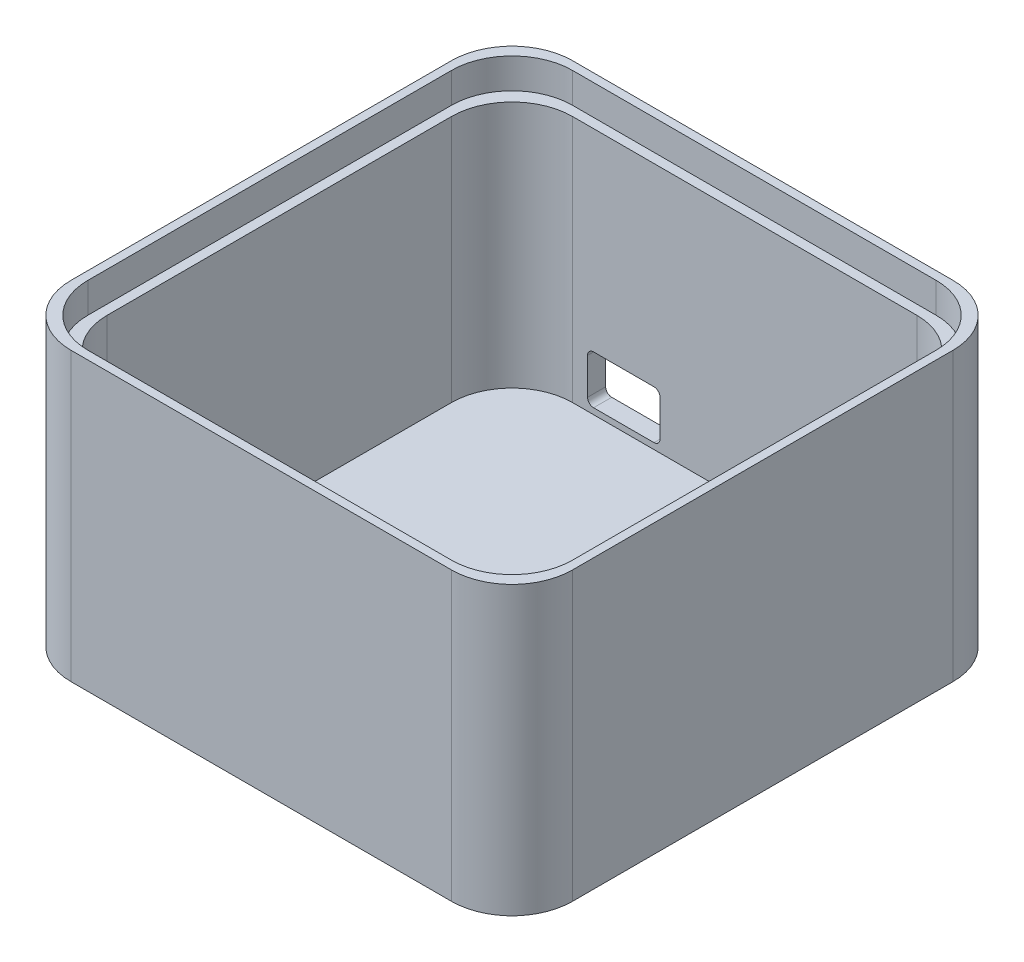
SolidWorks part; units mm, degrees
ref_plane "前视基准面" through (0, 0, 0) normal (0, 0, 1) x (1, 0, 0)
ref_plane "上视基准面" through (0, 0, 0) normal (0, 1, 0) x (1, 0, 0)
ref_plane "右视基准面" through (0, 0, 0) normal (1, 0, 0) x (0, 0, -1)
other "Configuration Table"
sketch "Sketch1" plane through (0, 0, 0) normal (0, 1, 0) x (1, 0, 0)
  line L1 (-30, 40) -> (30, 40)
  line L2 (-40, 30) -> (-40, -30)
  line L3 (-30, -40) -> (30, -40)
  line L4 (40, 30) -> (40, -30)
  line L5 (-40, 40) -> (40, -40) construction
  line L6 (-40, -40) -> (40, 40) construction
  line L7 (-31.5, 41.5) -> (31.5, 41.5)
  line L8 (-41.5, 31.5) -> (-41.5, -31.5)
  line L9 (-31.5, -41.5) -> (31.5, -41.5)
  line L10 (41.5, 31.5) -> (41.5, -31.5)
  line L11 (-41.5, 41.5) -> (41.5, -41.5) construction
  line L12 (-41.5, -41.5) -> (41.5, 41.5) construction
  line L13 (-28.5, 38.5) -> (28.5, 38.5)
  line L14 (-38.5, 28.5) -> (-38.5, -28.5)
  line L15 (-28.5, -38.5) -> (28.5, -38.5)
  line L16 (38.5, 28.5) -> (38.5, -28.5)
  line L17 (-38.5, 38.5) -> (38.5, -38.5) construction
  line L18 (-38.5, -38.5) -> (38.5, 38.5) construction
  arc A0 (30, -40) -> (40, -30) centre (30, -30) ccw
  arc A1 (28.5, -38.5) -> (38.5, -28.5) centre (28.5, -28.5) ccw
  arc A2 (31.5, -41.5) -> (41.5, -31.5) centre (31.5, -31.5) ccw
  arc A3 (-41.5, -31.5) -> (-31.5, -41.5) centre (-31.5, -31.5) ccw
  arc A4 (-40, -30) -> (-30, -40) centre (-30, -30) ccw
  arc A5 (-38.5, -28.5) -> (-28.5, -38.5) centre (-28.5, -28.5) ccw
  arc A6 (31.5, 41.5) -> (41.5, 31.5) centre (31.5, 31.5) cw
  arc A7 (30, 40) -> (40, 30) centre (30, 30) cw
  arc A8 (28.5, 38.5) -> (38.5, 28.5) centre (28.5, 28.5) cw
  arc A9 (-31.5, 41.5) -> (-41.5, 31.5) centre (-31.5, 31.5) ccw
  arc A10 (-30, 40) -> (-40, 30) centre (-30, 30) ccw
  arc A11 (-28.5, 38.5) -> (-38.5, 28.5) centre (-28.5, 28.5) ccw
  point P0 (0, 0)
  point P6 (0, 0)
  point P11 (0, 0)
  dimension "D7" = 10
  dimension "D1" = 80
  dimension "D2" = 80
  dimension "D3" = 1.5
  dimension "D4" = 1.5
  dimension "D5" = 3
  dimension "D6" = 3
extrude "Boss-Extrude1" add sketch "Sketch1" along normal blind 46 contours L7 A6 L10 A2 L9 A3 L8 A9 | L13 A8 L16 A1 L15 A5 L14 A11
sketch "Sketch2" plane through (0, 46, 0) normal (0, 1, 0) x (1, 0, 0)
  line L1 (-30.1, 40.1) -> (30.1, 40.1)
  line L2 (-40.1, 30.1) -> (-40.1, -30.1)
  line L3 (-30.1, -40.1) -> (30.1, -40.1)
  line L4 (40.1, 30.1) -> (40.1, -30.1)
  line L5 (-40.1, 40.1) -> (40.1, -40.1) construction
  line L6 (-40.1, -40.1) -> (40.1, 40.1) construction
  arc A0 (-40.1, -30.1) -> (-30.1, -40.1) centre (-30.1, -30.1) ccw
  arc A1 (30.1, -40.1) -> (40.1, -30.1) centre (30.1, -30.1) ccw
  arc A2 (30.1, 40.1) -> (40.1, 30.1) centre (30.1, 30.1) cw
  arc A3 (-30.1, 40.1) -> (-40.1, 30.1) centre (-30.1, 30.1) ccw
  point P0 (0, 0)
  dimension "D3" = 10
  dimension "D1" = 80.2
  dimension "D2" = 80.2
extrude "Cut-Extrude1" cut sketch "Sketch2" against normal blind 5
sketch "Sketch3" plane through (0, 0, 0) normal (0, -1, 0) x (1, 0, 0)
  line L1 (-31.5, 41.5) -> (31.5, 41.5)
  line L2 (-41.5, 31.5) -> (-41.5, -31.5)
  line L3 (-31.5, -41.5) -> (31.5, -41.5)
  line L4 (41.5, 31.5) -> (41.5, -31.5)
  line L5 (-41.5, 41.5) -> (41.5, -41.5) construction
  line L6 (-41.5, -41.5) -> (41.5, 41.5) construction
  arc A0 (-41.5, -31.5) -> (-31.5, -41.5) centre (-31.5, -31.5) ccw
  arc A1 (31.5, -41.5) -> (41.5, -31.5) centre (31.5, -31.5) ccw
  arc A2 (31.5, 41.5) -> (41.5, 31.5) centre (31.5, 31.5) cw
  arc A3 (-31.5, 41.5) -> (-41.5, 31.5) centre (-31.5, 31.5) ccw
  point P0 (0, 0)
  dimension "D3" = 10
  dimension "D1" = 83
  dimension "D2" = 83
extrude "Boss-Extrude2" add sketch "Sketch3" along normal blind 1.5
sketch "Sketch4" plane through (0, 0, -41.5) normal (0, 0, -1) x (-1, 0, 0)
  line L0 (0, 0) -> (0, 5)
  line L1 (0, 5) -> (-20, 5)
  line L2 (0, 5) -> (20, 5)
  line L4 (15, 1) -> (25, 1)
  line L5 (14, 2) -> (14, 8)
  line L6 (15, 9) -> (25, 9)
  line L7 (26, 2) -> (26, 8)
  line L8 (14, 1) -> (26, 9) construction
  line L9 (14, 9) -> (26, 1) construction
  circle A0 centre (-20, 5) radius 3
  arc A1 (25, 1) -> (26, 2) centre (25, 2) ccw
  arc A2 (15, 1) -> (14, 2) centre (15, 2) cw
  arc A3 (25, 9) -> (26, 8) centre (25, 8) cw
  arc A4 (14, 8) -> (15, 9) centre (15, 8) cw
  dimension "D4" = 6
  dimension "D7" = 1
  dimension "D1" = 20
  dimension "D2" = 5
  dimension "D3" = 20
  dimension "D5" = 8
  dimension "D6" = 12
extrude "Cut-Extrude2" cut sketch "Sketch4" against normal blind 8
